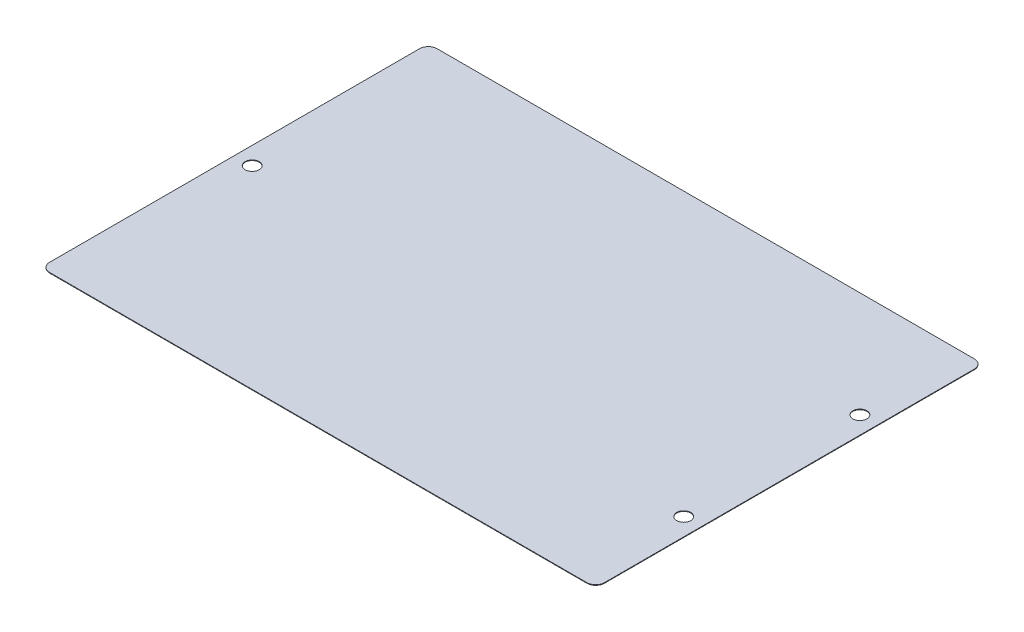
SolidWorks part; units mm, degrees
material "Rubber"
ref_plane "Front Plane" through (0, 0, 0) normal (0, 0, 1) x (1, 0, 0)
ref_plane "Top Plane" through (0, 0, 0) normal (0, 1, 0) x (1, 0, 0)
ref_plane "Right Plane" through (0, 0, 0) normal (1, 0, 0) x (0, 0, -1)
sketch "Sketch1" plane through (0, 0, 0) normal (0, 1, 0) x (1, 0, 0)
  line L0 (189, 66) -> (0, 66) construction
  line L1 (0, 132) -> (189, 132)
  line L2 (0, 132) -> (0, 0)
  line L3 (0, 0) -> (189, 0)
  line L4 (189, 132) -> (189, 0)
  line L5 (183, 36) -> (183, 96) construction
  circle A0 centre (6, 66) radius 2.4
  circle A1 centre (183, 36) radius 2.4
  circle A2 centre (183, 96) radius 2.4
  dimension "D4" = 4.8
  dimension "D1" = 189
  dimension "D2" = 132
  dimension "D3" = 6
  dimension "D5" = 60
  dimension "D6" = 6
extrude "Boss-Extrude1" add sketch "Sketch1" along normal blind 0.2
fillet "Fillet1" radius 3 4 edges at (0, 0.1, 0) (189, 0.1, 0) (189, 0.1, -132) (0, 0.1, -132)
